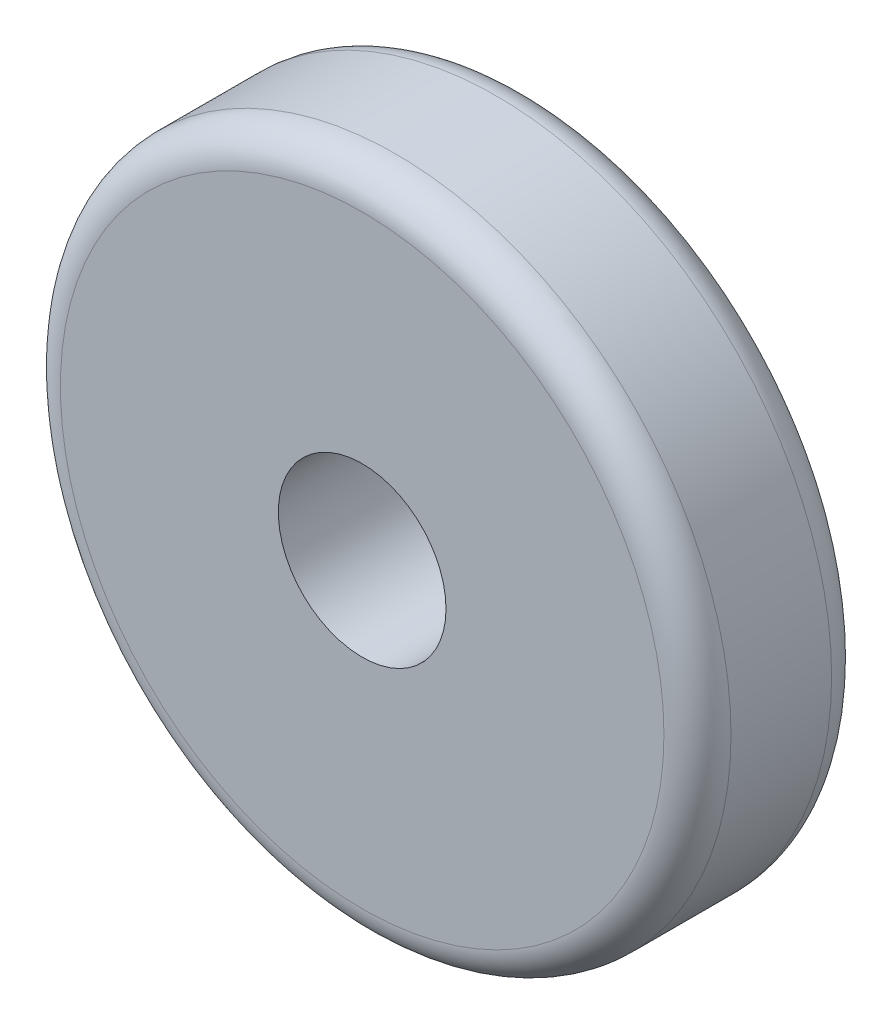
SolidWorks part; units mm, degrees
ref_plane "Plano frontal" through (0, 0, 0) normal (0, 0, 1) x (1, 0, 0)
ref_plane "Plano superior" through (0, 0, 0) normal (0, 1, 0) x (1, 0, 0)
ref_plane "Plano direito" through (0, 0, 0) normal (1, 0, 0) x (0, 0, -1)
sketch "Esboço1" plane through (0, 0, 0) normal (0, 0, 1) x (1, 0, 0)
  circle A0 centre (0, 0) radius 20
  dimension "D1" = 40
extrude "Ressalto-extrusão1" add sketch "Esboço1" along normal mid plane 10
sketch "Esboço2" plane through (0, 0, 0) normal (0, 0, 1) x (1, 0, 0)
  circle A0 centre (0, 0) radius 5
  dimension "D1" = 10
extrude "Corte-extrusão2" cut sketch "Esboço2" against normal mid plane 10 contours A0
fillet "Filete3" radius 2 2 edges at (20, 0, -5) (20, 0, 5)
